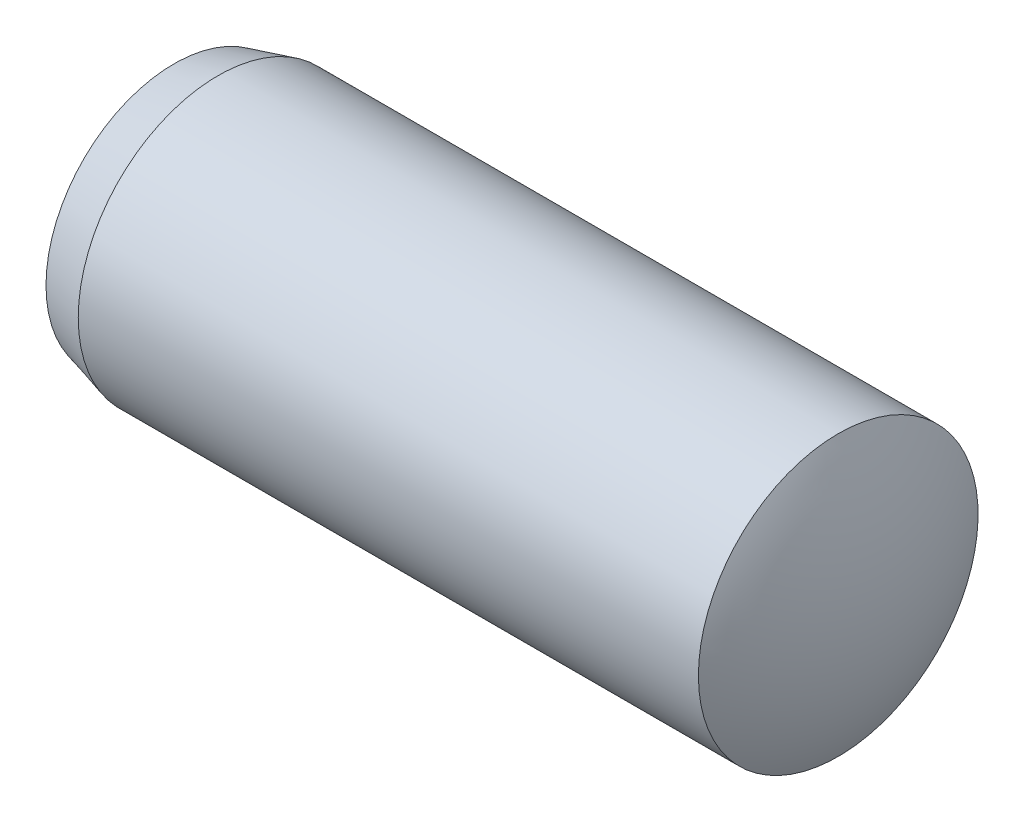
SolidWorks part; units mm, degrees
material "Сталь 45 ГОСТ 1050-88"
ref_plane "Спереди" through (0, 0, 0) normal (0, 0, 1) x (1, 0, 0)
ref_plane "Сверху" through (0, 0, 0) normal (0, 1, 0) x (1, 0, 0)
ref_plane "Справа" through (0, 0, 0) normal (1, 0, 0) x (0, 0, -1)
sketch "Эскиз1" plane through (0, 0, 0) normal (0, 0, 1) x (1, 0, 0)
  line L0 (-11.0225, 0) -> (2.172, 0) construction
  line L1 (-0.5, 2) -> (-9.37, 2)
  line L2 (-10, 1.8312) -> (-10, 0)
  line L3 (-10, 0) -> (0, 0)
  line L4 (-10, 1.8312) -> (-9.37, 2)
  arc A0 (0, 0) -> (-0.5, 2) centre (-4.25, 0) ccw
  dimension "D1" = 4
  dimension "D2" = 4.25
  dimension "D3" = 0.5
  dimension "D4" = 10
  dimension "D5" = 0.63
  dimension "D6" = 15
revolve "Повернуть1" add sketch "Эскиз1" angle 360 about L0
